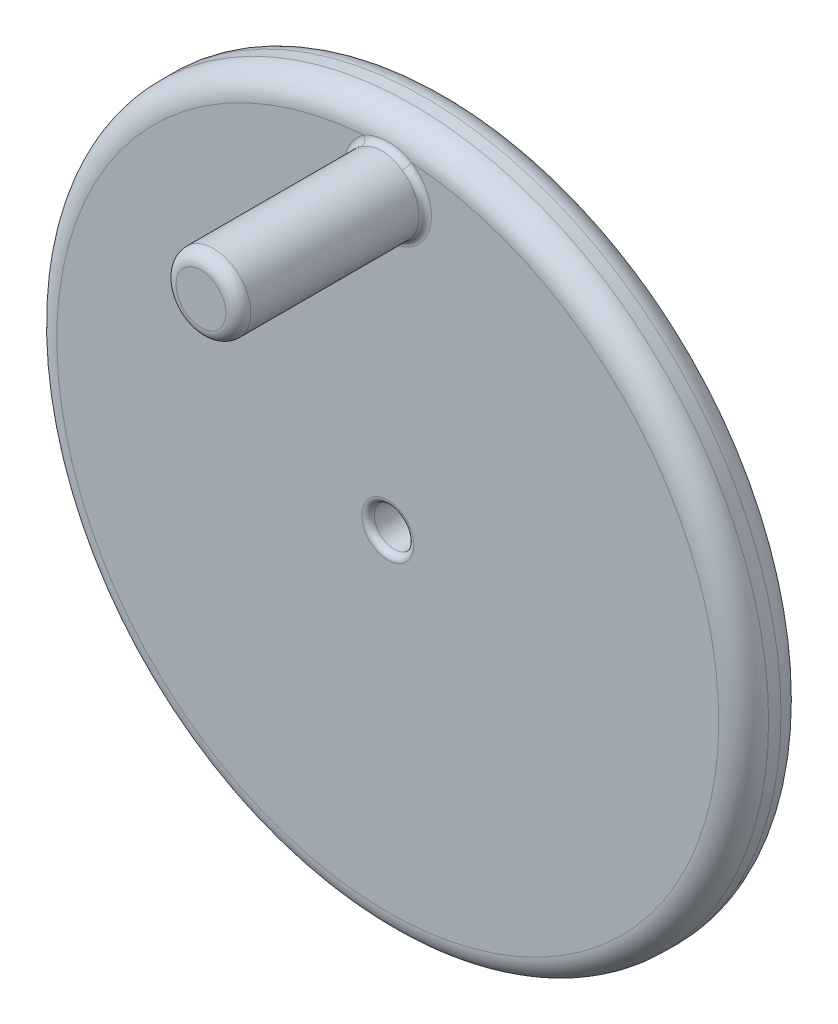
SolidWorks part; units mm, degrees
ref_plane "Front Plane" through (0, 0, 0) normal (0, 0, 1) x (1, 0, 0)
ref_plane "Top Plane" through (0, 0, 0) normal (0, 1, 0) x (1, 0, 0)
ref_plane "Right Plane" through (0, 0, 0) normal (1, 0, 0) x (0, 0, -1)
sketch "Sketch1" plane through (0, 0, 0) normal (0, 0, 1) x (1, 0, 0)
  circle A0 centre (0, 0) radius 57.15
  circle A1 centre (0, 0) radius 3.175
  dimension "D1" = 114.3
  dimension "D2" = 6.35
extrude "Boss-Extrude1" add sketch "Sketch1" along normal mid plane 10
fillet "Fillet1" radius 4 2 edges at (57.15, 0, -5) (57.15, 0, 5)
sketch "Sketch2" plane through (0, 0, 5) normal (0, 0, 1) x (1, 0, 0)
  circle A0 centre (0, 47.15) radius 6
  circle A1 centre (0, 0) radius 53.15 construction
  dimension "D1" = 12
extrude "Boss-Extrude2" add sketch "Sketch2" along normal blind 30
fillet "Fillet2" radius 2 1 edges at (6, 47.15, 35)
fillet "Fillet3" radius 1 3 edges at (3.175, 0, -5) (3.175, 0, 5) (6, 47.15, 5)
ref_plane "Plane1" through (-3.2791, 52.1747, 6) normal (0, 0, 1) x (1, 0, 0)
ref_plane "Plane2" through (3.8256, 53.0121, 5) normal (-0.9974, 0.072, 0) x (0, 0, 1)
